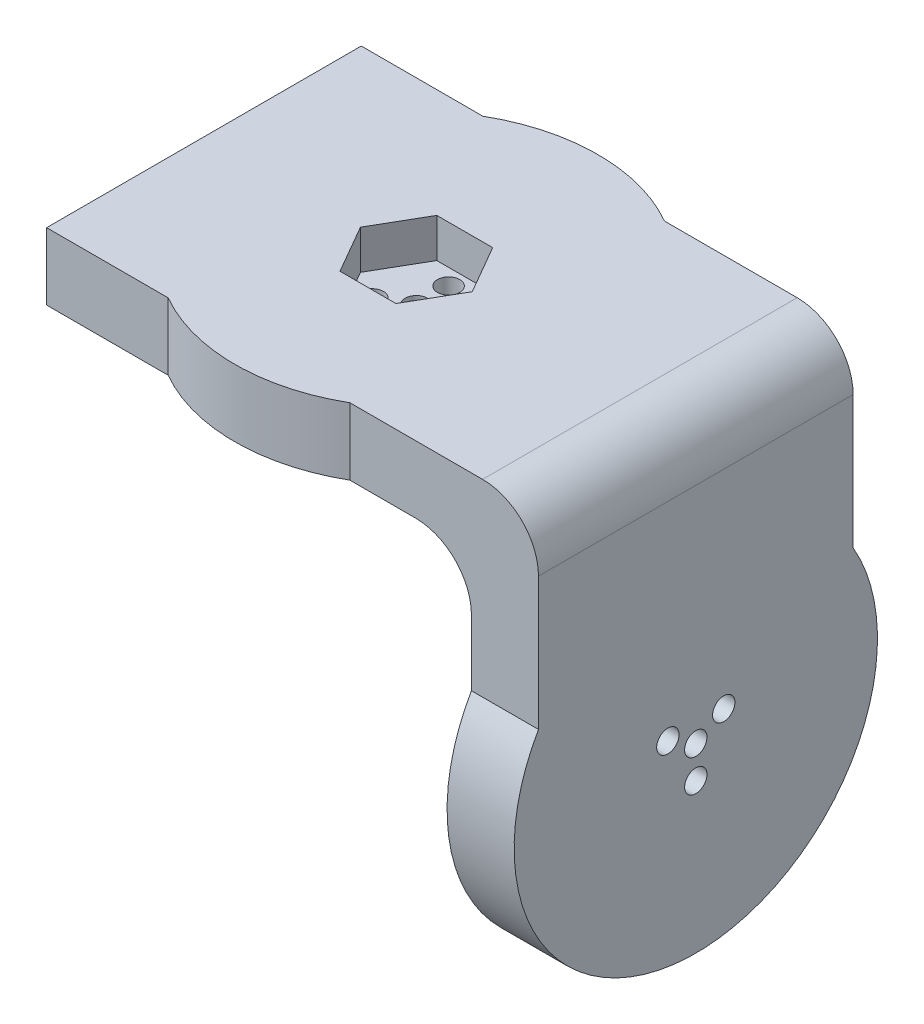
SolidWorks part; units mm, degrees
ref_plane "前视基准面" through (0, 0, 0) normal (0, 0, 1) x (1, 0, 0)
ref_plane "上视基准面" through (0, 0, 0) normal (0, 1, 0) x (1, 0, 0)
ref_plane "右视基准面" through (0, 0, 0) normal (1, 0, 0) x (0, 0, -1)
sketch "草图1" plane through (0, 0, 0) normal (0, 1, 0) x (1, 0, 0)
  line L0 (0, 0) -> (50, 0)
  line L1 (0, 0) -> (16.25, -28.1458)
  line L2 (0, 0) -> (16.25, 28.1458)
  line L3 (16.25, 28.1458) -> (50, 28.1458)
  line L4 (50, 28.1458) -> (50, -28.1458)
  line L5 (50, -28.1458) -> (16.25, -28.1458)
  circle A0 centre (0, 0) radius 32.5
extrude "凸台-拉伸1" add sketch "草图1" along normal blind 12 contours L2 A0 L1 | L1 A0 L0 | L0 A0 L2 | A0 L0 L4 L3 | A0 L5 L4 L0
sketch "草图2" plane through (0, 12, 0) normal (0, 1, 0) x (1, 0, 0)
  line L6 (5, -8.6603) -> (10, 0)
  line L7 (5, 8.6603) -> (10, 0)
  line L8 (5, 8.6603) -> (-5, 8.6603)
  line L9 (-5, 8.6603) -> (-10, 0)
  line L10 (-10, 0) -> (-5, -8.6603)
  line L11 (-5, -8.6603) -> (5, -8.6603)
extrude "切除-拉伸2" cut sketch "草图2" against normal blind 7
sketch "草图3" plane through (0, 0, 0) normal (0, -1, 0) x (1, 0, 0)
  line L6 (10, 0) -> (5, 8.6603)
  line L7 (5, 8.6603) -> (-5, 8.6603)
  line L8 (-5, 8.6603) -> (-10, 0)
  line L9 (-10, 0) -> (-5, -8.6603)
  line L10 (-5, -8.6603) -> (5, -8.6603)
  line L11 (5, -8.6603) -> (10, 0)
  circle A0 centre (0, 0) radius 2
  circle A1 centre (0, -5.7735) radius 2
  circle A2 centre (5, 2.8868) radius 2
  circle A3 centre (-5, 2.8868) radius 2
sketch "草图4" plane through (0, 0, 0) normal (0, -1, 0) x (1, 0, 0)
  line L0 (50, 28.1458) -> (38, 28.1458)
  line L1 (50, 28.1458) -> (16.25, 28.1458) construction
  line L2 (38, 28.1458) -> (38, -28.1458)
  line L3 (16.25, -28.1458) -> (50, -28.1458) construction
  line L4 (38, -28.1458) -> (50, -28.1458)
  line L5 (50, -28.1458) -> (50, 28.1458)
extrude "凸台-拉伸2" add sketch "草图4" along normal blind 85
sketch "草图6" plane through (50, 0, 0) normal (1, 0, 0) x (0, 0, -1)
  line L0 (0, 12) -> (0, -38)
  circle A0 centre (0, -38) radius 32.5
  line M3 (-28.1458, 12) -> (-28.1458, -85)
  line M5 (28.1458, -85) -> (28.1458, 12)
extrude "凸台-拉伸3" add sketch "草图6" against normal blind 12 contours A0 M3 | A0 M5
sketch "草图7" plane through (50, 0, 0) normal (1, 0, 0) x (0, 0, -1)
  line L0 (0, 12) -> (0, -38)
  line L1 (-28.1458, 12) -> (-28.1458, -85)
  line L2 (-28.1458, -85) -> (28.1458, -85)
  line L3 (28.1458, -85) -> (28.1458, 12)
  line L4 (28.1458, 12) -> (-28.1458, 12)
  circle A0 centre (0, -38) radius 32.5
  line M9 (-28.1458, -54.25) -> (-28.1458, -85)
  line M10 (-28.1458, -85) -> (28.1458, -85)
  line M11 (28.1458, -85) -> (28.1458, -54.25)
extrude "切除-拉伸4" cut sketch "草图7" against normal blind 12 contours A0 M9 M10 M11
fillet "圆角1" radius 10 1 edges at (38, 0, 0)
fillet "圆角2" radius 10 1 edges at (50, 12, 0)
sketch "草图8" plane through (50, 0, 0) normal (1, 0, 0) x (0, 0, -1)
  line L8 (10, -38) -> (5, -29.3397)
  line L9 (5, -29.3397) -> (-5, -29.3397)
  line L10 (-5, -29.3397) -> (-10, -38)
  line L11 (-10, -38) -> (-5, -46.6603)
  line L12 (-5, -46.6603) -> (5, -46.6603)
  line L13 (5, -46.6603) -> (10, -38)
  circle A0 centre (0, -38) radius 2
  circle A1 centre (0, -43.7735) radius 2
  circle A2 centre (5, -35.1132) radius 2
  circle A3 centre (-5, -35.1132) radius 2
extrude "切除-拉伸9" cut sketch "草图8" against normal blind 5 contours A3 | A0 | A2 | A1
sketch "草图10" plane through (38, 0, 0) normal (-1, 0, 0) x (0, 0, 1)
  line L8 (10, -38) -> (5, -29.3397)
  line L9 (5, -29.3397) -> (-5, -29.3397)
  line L10 (-10, -38) -> (-5, -29.3397)
  line L11 (-5, -46.6603) -> (-10, -38)
  line L12 (-5, -46.6603) -> (5, -46.6603)
  line L13 (5, -46.6603) -> (10, -38)
extrude "切除-拉伸7" cut sketch "草图10" against normal blind 7
extrude "切除-拉伸8" cut sketch "草图3" against normal blind 5 contours A3 | A2 | A0 | A1
sketch "草图12" plane through (0, 12, 0) normal (0, 1, 0) x (1, 0, 0)
  line L0 (0, 0) -> (-38, 0)
  line L1 (0, 0) -> (-16.25, 28.1458)
  line L2 (0, 0) -> (-16.25, -28.1458)
  line L3 (-38, 0) -> (-38, 28.1458)
  line L4 (-38, 28.1458) -> (-16.25, 28.1458)
  line L5 (-38, 0) -> (-38, -28.1458)
  line L6 (-38, -28.1458) -> (-16.25, -28.1458)
  arc A0 (16.25, 28.1458) -> (16.25, -28.1458) centre (0, 0) ccw construction
  arc M15 (16.25, 28.1458) -> (16.25, -28.1458) centre (0, 0) ccw
extrude "凸台-拉伸5" add sketch "草图12" against normal blind 12 contours L5 L6 L0 M15 | L4 L3 L0 M15
sketch "草图13" plane through (-38, 0, 0) normal (-1, 0, 0) x (0, 0, 1)
  line L0 (0, 0) -> (0, 12)
  line L1 (0, 0) -> (0, 6)
  line L2 (0, 6) -> (20, 6)
  line L3 (0, 6) -> (-20, 6)
  circle A0 centre (-20, 6) radius 3
  circle A1 centre (20, 6) radius 3
  circle A2 centre (0, 6) radius 3
extrude "切除-拉伸11" cut sketch "草图13" against normal blind 15
